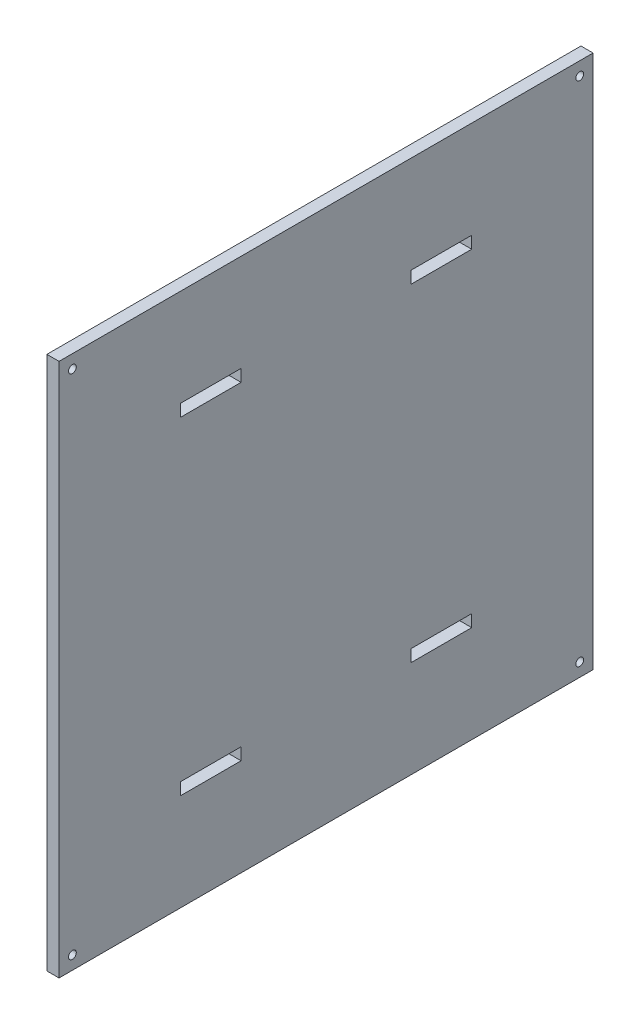
SolidWorks part; units mm, degrees
ref_plane "前视基准面" through (0, 0, 0) normal (0, 0, 1) x (1, 0, 0)
ref_plane "上视基准面" through (0, 0, 0) normal (0, 1, 0) x (1, 0, 0)
ref_plane "右视基准面" through (0, 0, 0) normal (1, 0, 0) x (0, 0, -1)
sketch "草图1" plane through (0, 0, 0) normal (1, 0, 0) x (0, 0, -1)
  line L1 (0, 0) -> (-220, 0)
  line L2 (0, 0) -> (0, 220)
  line L3 (0, 220) -> (-220, 220)
  line L4 (-220, 0) -> (-220, 220)
  line L5 (-170, 45) -> (-145, 45)
  line L6 (-170, 45) -> (-170, 40)
  line L7 (-170, 40) -> (-145, 40)
  line L8 (-145, 45) -> (-145, 40)
  line L9 (-75, 45) -> (-50, 45)
  line L10 (-75, 45) -> (-75, 40)
  line L11 (-75, 40) -> (-50, 40)
  line L12 (-50, 45) -> (-50, 40)
  line L13 (-170, 180) -> (-145, 180)
  line L14 (-170, 180) -> (-170, 175)
  line L15 (-170, 175) -> (-145, 175)
  line L16 (-145, 180) -> (-145, 175)
  line L17 (-75, 180) -> (-50, 180)
  line L18 (-75, 180) -> (-75, 175)
  line L19 (-75, 175) -> (-50, 175)
  line L20 (-50, 180) -> (-50, 175)
  circle A0 centre (-214.5, 214.5) radius 1.6
  circle A1 centre (-5.5, 214.5) radius 1.6
  circle A2 centre (-214.5, 5.5) radius 1.6
  circle A3 centre (-5.5, 5.5) radius 1.6
  point P21 (-170, 42.5)
  dimension "D19" = 3.2
  dimension "D20" = 3.2
  dimension "D21" = 3.2
  dimension "D22" = 3.2
  dimension "D1" = 220
  dimension "D2" = 220
  dimension "D3" = 5
  dimension "D4" = 5
  dimension "D5" = 5
  dimension "D6" = 5
  dimension "D7" = 25
  dimension "D8" = 25
  dimension "D9" = 25
  dimension "D10" = 25
  dimension "D11" = 140
  dimension "D12" = 140
  dimension "D13" = 70
  dimension "D14" = 70
  dimension "D15" = 40
  dimension "D16" = 40
  dimension "D17" = 50
  dimension "D18" = 50
  dimension "D23" = 209
  dimension "D24" = 209
  dimension "D25" = 209
  dimension "D26" = 5.5
  dimension "D27" = 5.5
  dimension "D28" = 5.5
  dimension "D29" = 5.5
  dimension "D30" = 5.5
  dimension "D31" = 295.5706
extrude "凸台-拉伸1" add sketch "草图1" along normal blind 5
